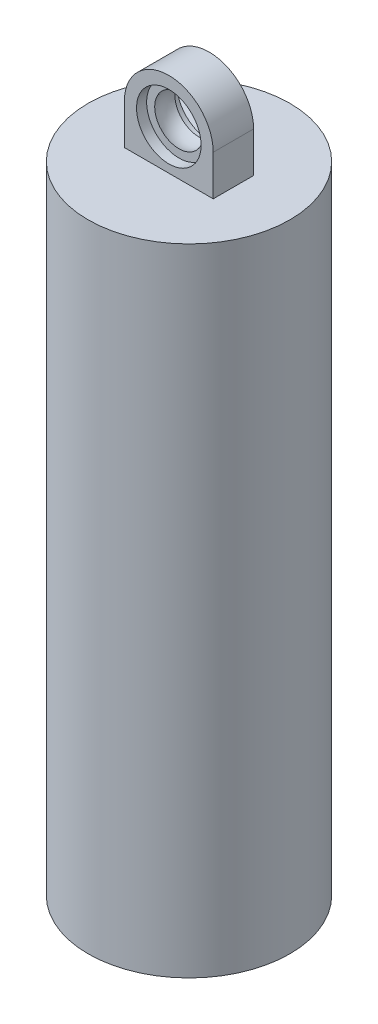
SolidWorks part; units mm, degrees
ref_plane "前视基准面" through (0, 0, 0) normal (0, 0, 1) x (1, 0, 0)
ref_plane "上视基准面" through (0, 0, 0) normal (0, 1, 0) x (1, 0, 0)
ref_plane "右视基准面" through (0, 0, 0) normal (1, 0, 0) x (0, 0, -1)
sketch "草图1" plane through (0, 0, 0) normal (0, 1, 0) x (1, 0, 0)
  circle A0 centre (0, 0) radius 25
  dimension "D1" = 50
extrude "凸台-拉伸1" add sketch "草图1" along normal blind 157.5
sketch "草图2" plane through (0, 0, 0) normal (0, -1, 0) x (1, 0, 0)
  circle A0 centre (0, 0) radius 12.5
  dimension "D1" = 25
extrude "凸台-拉伸2" add sketch "草图2" along normal blind 6
sketch "草图3" plane through (0, -6, 0) normal (0, -1, 0) x (1, 0, 0)
  circle A0 centre (0, 0) radius 6
  dimension "D1" = 12
extrude "切除-拉伸1" cut sketch "草图3" against normal blind 80
sketch "草图4" plane through (0, 0, 0) normal (0, 0, 1) x (1, 0, 0)
  line L0 (25, 157.5) -> (-25, 157.5) construction
  line L1 (-11, 157.5) -> (11, 157.5)
  line L2 (-11, 157.5) -> (-11, 167.5)
  line L4 (11, 157.5) -> (11, 167.5)
  line L5 (0, 193.283) -> (0, 138.3299) construction
  arc A0 (-11, 167.5) -> (11, 167.5) centre (0, 167.5) cw
  circle A1 centre (0, 167.5) radius 8
  dimension "D4" = 16
  dimension "D5" = 10
  dimension "D1" = 22
  dimension "D2" = 11
  dimension "D3" = 10
extrude "凸台-拉伸3" add sketch "草图4" against normal mid plane 10
sketch "草图5" plane through (0, 0, 0) normal (0, 0, 1) x (1, 0, 0)
  circle A0 centre (0, 167.5) radius 8
extrude "凸台-拉伸4" add sketch "草图5" along normal mid plane 5
ref_plane "基准面4" through (0, 0, 4.5) normal (0, 0, 1) x (1, 0, 0)
sketch "草图7" plane through (0, 0, 2.5) normal (0, 0, 1) x (1, 0, 0)
  circle A0 centre (0, 167.5) radius 6
  dimension "D1" = 12
sketch "草图8" plane through (0, 0, 4.5) normal (0, 0, 1) x (1, 0, 0)
  circle A0 centre (0, 167.5) radius 4
  dimension "D1" = 8
loft "放样1" add profiles "草图8", "草图7"
mirror "镜向1" about plane through (0, 0, 0) normal (0, 0, 1) of "放样1"
sketch "草图9" plane through (0, 0, 4.5) normal (0, 0, 1) x (1, 0, 0)
  circle A0 centre (0, 167.5) radius 2.5
  circle A1 centre (0, 167.5) radius 4 construction
  dimension "D1" = 5
extrude "切除-拉伸2" cut sketch "草图9" against normal blind 31
sketch "草图10" plane through (0, 0, 4.5) normal (0, 0, 1) x (1, 0, 0)
  circle A0 centre (0, 167.5) radius 6
extrude "切除-拉伸3" cut sketch "草图10" against normal blind 17
sketch "草图11" plane through (0, 0, 0) normal (0, 0, 1) x (1, 0, 0)
  line L0 (0, 174) -> (0, 161)
  arc A0 (0, 161) -> (0, 174) centre (0, 167.5) ccw
  dimension "D1" = 13
revolve "切除-旋转1" cut sketch "草图11" angle 360 about L0
